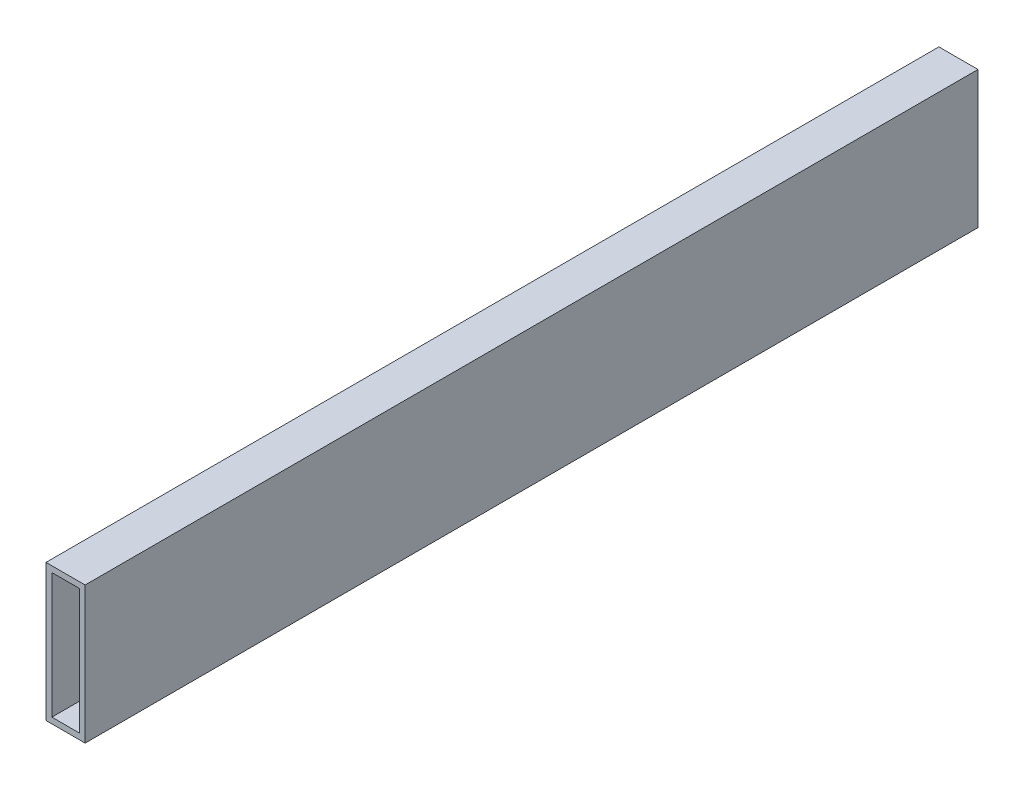
SolidWorks part; units mm, degrees
material "1060 Alloy"
ref_plane "Front Plane" through (0, 0, 0) normal (0, 0, 1) x (1, 0, 0)
ref_plane "Top Plane" through (0, 0, 0) normal (0, 1, 0) x (1, 0, 0)
ref_plane "Right Plane" through (0, 0, 0) normal (1, 0, 0) x (0, 0, -1)
sketch "Sketch1" plane through (0, 0, 0) normal (0, 0, 1) x (1, 0, 0)
  line L0 (0, 70) -> (3, 70)
  line L1 (0, 0) -> (20, 0)
  line L2 (0, 0) -> (0, 70)
  line L3 (0, 70) -> (20, 70)
  line L4 (20, 0) -> (20, 70)
  line L5 (3, 70) -> (3, 0)
  line L6 (0, 0) -> (0, 3)
  line L7 (0, 3) -> (20, 3)
  line L8 (20, 0) -> (17, 0)
  line L9 (17, 0) -> (17, 70)
  line L10 (20, 70) -> (20, 67)
  line L11 (20, 67) -> (0, 67)
extrude "Boss-Extrude1" add sketch "Sketch1" against normal up to surface (50 mm away) contours L5 L11 L2 L7 | L11 L5 L0 L2 | L11 L9 L3 L5 | L11 L4 L3 L9 | L4 L11 L9 L7 | L1 L9 L7 L5 | L7 L2 L1 L5 | L9 L1 L4 L7
sketch "Sketch2" plane through (0, 0, 0) normal (0, 0, 1) x (1, 0, 0)
  line L0 (3, 3) -> (17, 3) construction
  line L1 (17, 3) -> (17, 67) construction
  line L2 (17, 67) -> (3, 67) construction
  line L3 (3, 67) -> (3, 3) construction
  line L4 (20, 0) -> (20, 70)
  line L5 (20, 70) -> (0, 70)
  line L6 (0, 70) -> (0, 0)
  line L7 (0, 0) -> (20, 0)
  line L8 (20, 0) -> (20, 70)
  line L9 (20, 70) -> (0, 70)
  line L10 (0, 70) -> (0, 0)
  line L11 (0, 0) -> (20, 0)
  line L12 (3, 3) -> (17, 3)
  line L13 (17, 3) -> (17, 67)
  line L14 (17, 67) -> (3, 67)
  line L15 (3, 67) -> (3, 3)
  dimension "D1" = 0
extrude "Boss-Extrude2" add sketch "Sketch2" along normal up to surface (406.2937 mm away)
